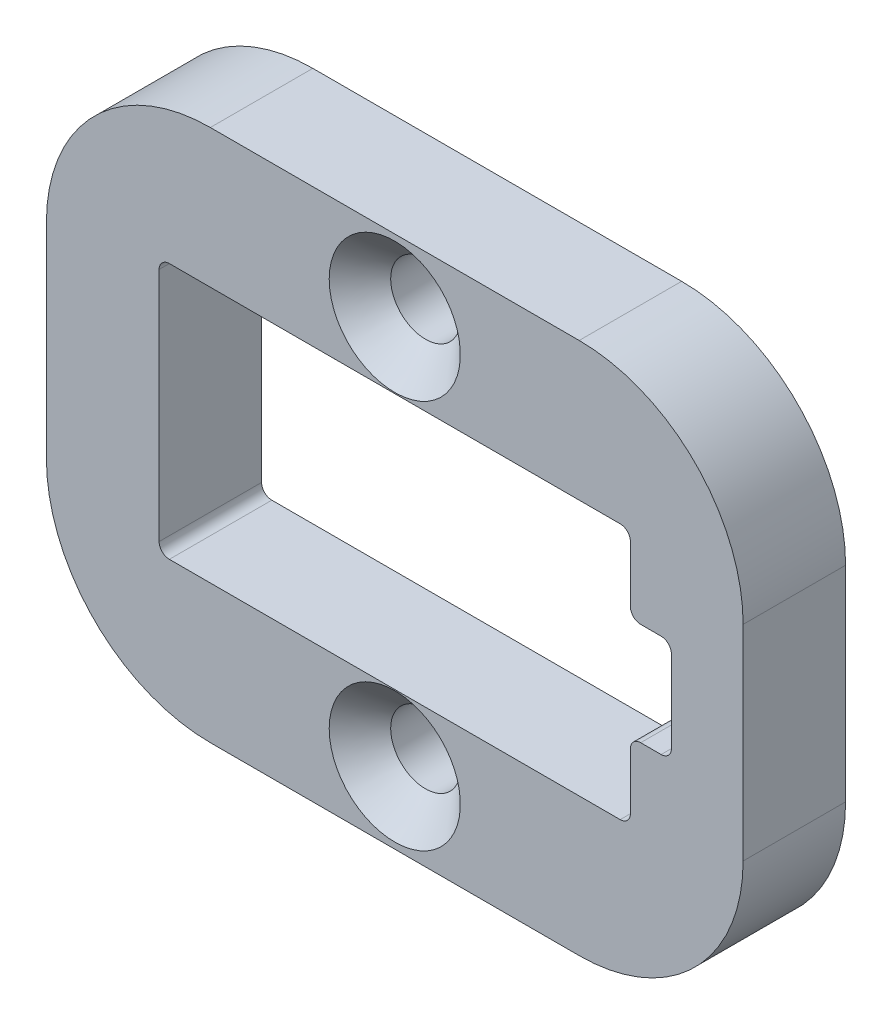
SolidWorks part; units mm, degrees
material "PLA"
ref_plane "Front Plane" through (0, 0, 0) normal (0, 0, 1) x (1, 0, 0)
ref_plane "Top Plane" through (0, 0, 0) normal (0, 1, 0) x (1, 0, 0)
ref_plane "Right Plane" through (0, 0, 0) normal (1, 0, 0) x (0, 0, -1)
other "Graphic1"
other "Graphic (Closed) -1"
sketch "Sketch1" plane through (0, 0, 0) normal (0, 0, 1) x (1, 0, 0)
  line L0 (34.17, 18.13) -> (34.17, 8.13)
  line L1 (26.17, 26.13) -> (8.17, 26.13)
  line L2 (26.17, 0.13) -> (8.17, 0.13)
  line L3 (30.17, 15.63) -> (29.17, 15.63)
  line L4 (0.17, 8.13) -> (0.17, 18.13)
  line L5 (6.17, 19.38) -> (28.17, 19.38)
  line L6 (5.67, 18.88) -> (5.67, 7.38)
  line L7 (6.17, 6.88) -> (28.17, 6.88)
  line L8 (28.67, 18.88) -> (28.67, 16.13)
  line L9 (30.67, 15.13) -> (30.67, 11.13)
  line L10 (28.67, 10.13) -> (28.67, 7.38)
  line L11 (30.17, 10.63) -> (29.17, 10.63)
  arc A0 (0.17, 18.13) -> (8.17, 26.13) centre (8.17, 18.13) cw
  arc A1 (8.17, 0.13) -> (0.17, 8.13) centre (8.17, 8.13) cw
  arc A2 (34.17, 8.13) -> (26.17, 0.13) centre (26.17, 8.13) cw
  arc A3 (26.17, 26.13) -> (34.17, 18.13) centre (26.17, 18.13) cw
  arc A4 (29.17, 10.63) -> (28.67, 10.13) centre (29.17, 10.13) ccw
  arc A5 (30.67, 11.13) -> (30.17, 10.63) centre (30.17, 11.13) cw
  arc A6 (30.17, 15.63) -> (30.67, 15.13) centre (30.17, 15.13) cw
  arc A7 (28.67, 16.13) -> (29.17, 15.63) centre (29.17, 16.13) ccw
  arc A8 (28.67, 7.38) -> (28.17, 6.88) centre (28.17, 7.38) cw
  arc A9 (28.17, 19.38) -> (28.67, 18.88) centre (28.17, 18.88) cw
  arc A10 (5.67, 7.38) -> (6.17, 6.88) centre (6.17, 7.38) ccw
  arc A11 (6.17, 19.38) -> (5.67, 18.88) centre (6.17, 18.88) ccw
  circle A12 centre (17.17, 3.63) radius 1.7
  circle A13 centre (17.17, 22.63) radius 1.7
  dimension "D1" = 8
  dimension "D2" = 0.5
  dimension "D3" = 0.5
  dimension "D4" = 0.5
  dimension "D5" = 22
extrude "Boss-Extrude1" add sketch "Sketch1" along normal blind 5
chamfer "Chamfer1" distance 1.5 angle 45 2 edges at (18.87, 3.63, 5) (18.87, 22.63, 5)
